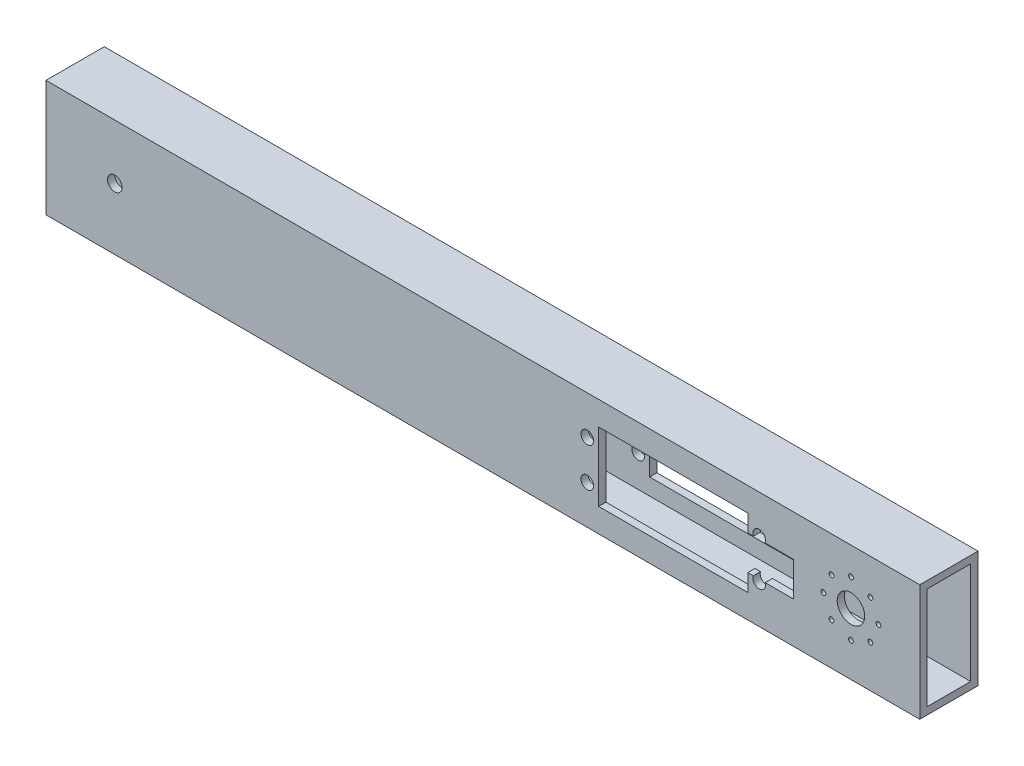
SolidWorks part; units mm, degrees
material "6061-T6 (SS)"
ref_plane "Front Plane" through (0, 0, 0) normal (0, 0, 1) x (1, 0, 0)
ref_plane "Top Plane" through (0, 0, 0) normal (0, 1, 0) x (1, 0, 0)
ref_plane "Right Plane" through (0, 0, 0) normal (1, 0, 0) x (0, 0, -1)
sketch "Sketch1" plane through (0, 0, 0) normal (0, 1, 0) x (1, 0, 0)
  line L1 (-381, 25.4) -> (0, 25.4)
  line L2 (-381, 25.4) -> (-381, 0)
  line L3 (-381, 0) -> (0, 0)
  line L4 (0, 25.4) -> (0, 0)
  dimension "D1" = 381
  dimension "D2" = 25.4
extrude "Boss-Extrude1" add sketch "Sketch1" along normal blind 50.8
sketch "Sketch2" plane through (-381, 0, 0) normal (-1, 0, 0) x (0, 0, 1)
  line L0 (-25.4, 50.8) -> (0, 50.8) construction
  line L1 (-22.225, 47.625) -> (-3.175, 47.625)
  line L2 (-22.225, 47.625) -> (-22.225, 3.175)
  line L3 (-22.225, 3.175) -> (-3.175, 3.175)
  line L4 (-3.175, 47.625) -> (-3.175, 3.175)
  line L5 (-25.4, 50.8) -> (-25.4, 0) construction
  line L6 (0, 50.8) -> (0, 0) construction
  line L7 (-25.4, 0) -> (0, 0) construction
  dimension "D1" = 3.175
  dimension "D2" = 3.175
  dimension "D3" = 3.175
  dimension "D4" = 3.175
extrude "Cut-Extrude1" cut sketch "Sketch2" against normal through all
sketch "Sketch3" plane through (0, 0, -25.4) normal (0, 0, -1) x (-1, 0, 0)
  line L2 (717.7479, 26.8481) -> (635.4271, 26.8481) construction
  line L3 (381, 50.8) -> (381, 0) construction
  line L4 (190.5, 0) -> (190.5, 50.8) construction
  line L5 (0, 50.8) -> (381, 50.8) construction
  line L6 (0, 0) -> (381, 0) construction
  circle A0 centre (351, 26.8481) radius 3.175
  circle A1 centre (30, 26.8481) radius 3.175
  dimension "D1" = 6.35
  dimension "D2" = 30
extrude "Cut-Extrude2" cut sketch "Sketch3" against normal through all
sketch "Sketch4" plane through (0, 0, 0) normal (0, 0, 1) x (1, 0, 0)
  line L0 (0, 25.4) -> (-75, 25.4)
  line L1 (0, 50.8) -> (0, 0) construction
  dimension "D1" = 75
sketch "Sketch5" plane through (0, 0, 0) normal (0, 0, 1) x (1, 0, 0)
  line L0 (-75, 32.9) -> (-75, 40.4)
  line L1 (-140, 10.4) -> (-75, 10.4)
  line L2 (-140, 10.4) -> (-140, 40.4)
  line L3 (-140, 40.4) -> (-75, 40.4)
  line L4 (-75, 10.4) -> (-75, 17.9)
  line L5 (0, 50.8) -> (0, 0) construction
  line L6 (-75, 32.9) -> (-55, 32.9)
  line L8 (-75, 17.9) -> (-55, 17.9)
  line L9 (-55, 32.9) -> (-55, 17.9)
  point P9 (-55, 25.4)
  point P10 (-140, 25.4)
  dimension "D1" = 30
  dimension "D2" = 65
  dimension "D3" = 15
  dimension "D4" = 20
  dimension "D5" = 75
extrude "Cut-Extrude3" cut sketch "Sketch5" along normal up to surface and the other way through all from surface
sketch "Sketch7" plane through (0, 0, 0) normal (0, 0, 1) x (1, 0, 0)
  line L0 (-112.2285, 50.8) -> (-112.2285, 0) construction
  line L1 (-381, 50.8) -> (0, 50.8) construction
  line L2 (-381, 0) -> (0, 0) construction
  line L3 (-143.9767, 25.4) -> (-80.4804, 25.4) construction
  line L4 (-145, 33.9826) -> (-145, 16.9826) construction
  line L5 (-140, 40.4) -> (-140, 10.4) construction
  circle A0 centre (-145, 33.9826) radius 2.75
  circle A1 centre (-70, 33.9826) radius 2.75
  circle A2 centre (-145, 16.9826) radius 2.75
  circle A3 centre (-70, 16.9826) radius 2.75
  point P4 (-112.2285, 25.4)
  dimension "D1" = 5.5
  dimension "D2" = 75
  dimension "D3" = 17
  dimension "D4" = 5
extrude "Cut-Extrude4" cut sketch "Sketch7" against normal through all
sketch "Sketch8" plane through (0, 0, 0) normal (0, 0, 1) x (1, 0, 0)
  circle A0 centre (-30, 26.8481) radius 6
  circle A1 centre (-30, 26.8481) radius 3.175 construction
  circle A2 centre (-30, 38.8481) radius 1.05
  circle A3 centre (-21.5147, 35.3333) radius 1.05
  circle A4 centre (-18, 26.8481) radius 1.05
  circle A5 centre (-21.5147, 18.3628) radius 1.05
  circle A6 centre (-30, 14.8481) radius 1.05
  circle A7 centre (-38.4853, 18.3628) radius 1.05
  circle A8 centre (-42, 26.8481) radius 1.05
  circle A9 centre (-38.4853, 35.3333) radius 1.05
  point P24 (-30, 26.8481)
  dimension "D1" = 12
  dimension "D2" = 2.1
  dimension "D3" = 12
  dimension "D4" = 8
extrude "Cut-Extrude5" cut sketch "Sketch8" against normal up to next
